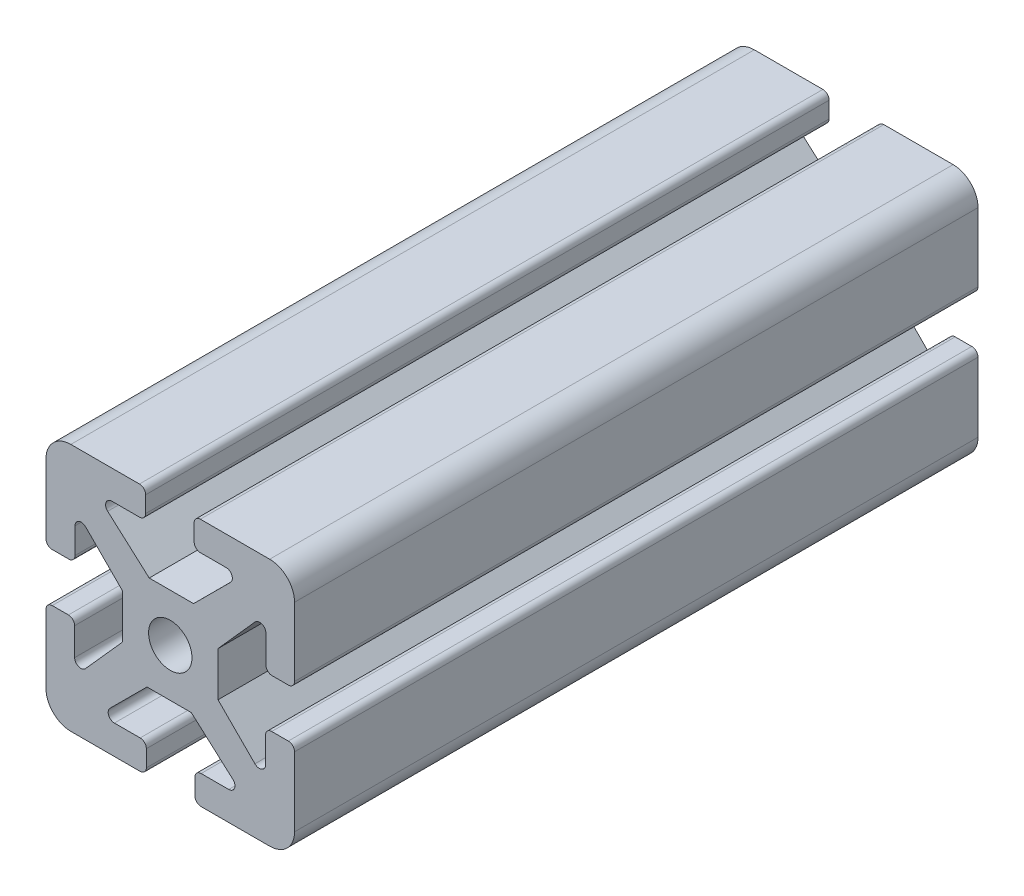
SolidWorks part; units mm, degrees
ref_plane "Front Plane" through (0, 0, 0) normal (0, 0, 1) x (1, 0, 0)
ref_plane "Top Plane" through (0, 0, 0) normal (0, 1, 0) x (1, 0, 0)
ref_plane "Right Plane" through (0, 0, 0) normal (1, 0, 0) x (0, 0, -1)
sketch "Sketch2" plane through (0, 0, 0) normal (0, 0, 1) x (1, 0, 0)
  line L0 (46.607, 139.3199) -> (233.0351, 139.3199) construction
  line L1 (0, 40) -> (40, 0) construction
  line L2 (0, 0) -> (40, 0) construction
  line L3 (0, 0) -> (0, 40) construction
  line L4 (0, 40) -> (40, 40) construction
  line L5 (40, 0) -> (40, 40) construction
  line L6 (0, 0) -> (40, 40) construction
  line L7 (19.4883, 27.6847) -> (23.7499, 27.6847)
  line L8 (23.7499, 27.6847) -> (29.6997, 33.625)
  line L9 (28.9931, 35.3327) -> (24.8456, 35.3327)
  line L10 (23.8456, 36.3327) -> (23.8456, 39)
  line L11 (24.8456, 40) -> (36, 40)
  line L12 (40, 36) -> (40, 24.9611)
  line L13 (39, 23.9611) -> (36.3883, 23.9611)
  line L14 (35.3883, 24.9611) -> (35.3883, 29.4086)
  line L15 (33.6417, 30.0739) -> (27.6847, 23.3888)
  line L16 (27.6847, 23.3888) -> (27.6847, 20.5117)
  line L17 (27.6847, 16.2501) -> (33.625, 10.3003)
  line L18 (30.0739, 6.3583) -> (23.3888, 12.3153)
  line L19 (27.6847, 20.5117) -> (27.6847, 16.2501)
  line L20 (35.3327, 11.0069) -> (35.3327, 15.1544)
  line L21 (36.3327, 16.1544) -> (39, 16.1544)
  line L22 (40, 15.1544) -> (40, 4)
  line L23 (36, 0) -> (24.9611, 0)
  line L24 (23.9611, 1) -> (23.9611, 3.6117)
  line L25 (24.9611, 4.6117) -> (29.4086, 4.6117)
  line L26 (23.3888, 12.3153) -> (20.5117, 12.3153)
  line L27 (16.2501, 12.3153) -> (10.3003, 6.375)
  line L28 (6.3583, 9.9261) -> (12.3153, 16.6112)
  line L29 (20.5117, 12.3153) -> (16.2501, 12.3153)
  line L30 (11.0069, 4.6673) -> (15.1544, 4.6673)
  line L31 (16.1544, 3.6673) -> (16.1544, 1)
  line L32 (15.1544, 0) -> (4, 0)
  line L33 (0, 4) -> (0, 15.0389)
  line L34 (1, 16.0389) -> (3.6117, 16.0389)
  line L35 (4.6117, 15.0389) -> (4.6117, 10.5914)
  line L36 (12.3153, 16.6112) -> (12.3153, 19.4883)
  line L37 (12.3153, 23.7499) -> (6.375, 29.6997)
  line L38 (9.9261, 33.6417) -> (16.6112, 27.6847)
  line L39 (12.3153, 19.4883) -> (12.3153, 23.7499)
  line L40 (4.6673, 28.9931) -> (4.6673, 24.8456)
  line L41 (3.6673, 23.8456) -> (1, 23.8456)
  line L42 (0, 24.8456) -> (0, 36)
  line L43 (4, 40) -> (15.0389, 40)
  line L44 (16.0389, 39) -> (16.0389, 36.3883)
  line L45 (15.0389, 35.3883) -> (10.5914, 35.3883)
  line L46 (16.6112, 27.6847) -> (19.4883, 27.6847)
  circle A1 centre (20, 20) radius 3.4925
  arc A2 (40, 24.9611) -> (39, 23.9611) centre (39, 24.9611) cw
  arc A3 (36.3883, 23.9611) -> (35.3883, 24.9611) centre (36.3883, 24.9611) cw
  arc A4 (24.8456, 35.3327) -> (23.8456, 36.3327) centre (24.8456, 36.3327) cw
  arc A5 (23.8456, 39) -> (24.8456, 40) centre (24.8456, 39) cw
  arc A6 (29.6997, 33.625) -> (28.9931, 35.3327) centre (28.9931, 34.3327) ccw
  arc A7 (35.3883, 29.4086) -> (33.6417, 30.0739) centre (34.3883, 29.4086) ccw
  arc A8 (40, 36) -> (36, 40) centre (36, 36) ccw
  arc A9 (35.3327, 15.1544) -> (36.3327, 16.1544) centre (36.3327, 15.1544) cw
  arc A10 (39, 16.1544) -> (40, 15.1544) centre (39, 15.1544) cw
  arc A11 (36, 0) -> (40, 4) centre (36, 4) ccw
  arc A12 (24.9611, 0) -> (23.9611, 1) centre (24.9611, 1) cw
  arc A13 (23.9611, 3.6117) -> (24.9611, 4.6117) centre (24.9611, 3.6117) cw
  arc A14 (29.4086, 4.6117) -> (30.0739, 6.3583) centre (29.4086, 5.6117) ccw
  arc A15 (33.625, 10.3003) -> (35.3327, 11.0069) centre (34.3327, 11.0069) ccw
  arc A16 (15.1544, 4.6673) -> (16.1544, 3.6673) centre (15.1544, 3.6673) cw
  arc A17 (16.1544, 1) -> (15.1544, 0) centre (15.1544, 1) cw
  arc A18 (0, 4) -> (4, 0) centre (4, 4) ccw
  arc A19 (0, 15.0389) -> (1, 16.0389) centre (1, 15.0389) cw
  arc A20 (3.6117, 16.0389) -> (4.6117, 15.0389) centre (3.6117, 15.0389) cw
  arc A21 (4.6117, 10.5914) -> (6.3583, 9.9261) centre (5.6117, 10.5914) ccw
  arc A22 (10.3003, 6.375) -> (11.0069, 4.6673) centre (11.0069, 5.6673) ccw
  arc A23 (4.6673, 24.8456) -> (3.6673, 23.8456) centre (3.6673, 24.8456) cw
  arc A24 (1, 23.8456) -> (0, 24.8456) centre (1, 24.8456) cw
  arc A25 (4, 40) -> (0, 36) centre (4, 36) ccw
  arc A26 (15.0389, 40) -> (16.0389, 39) centre (15.0389, 39) cw
  arc A27 (16.0389, 36.3883) -> (15.0389, 35.3883) centre (15.0389, 36.3883) cw
  arc A28 (10.5914, 35.3883) -> (9.9261, 33.6417) centre (10.5914, 34.3883) ccw
  arc A29 (6.375, 29.6997) -> (4.6673, 28.9931) centre (5.6673, 28.9931) ccw
  point P24 (40, 23.9611)
  point P31 (23.8456, 40)
  dimension "D1" = 40
  dimension "D3" = 1
  dimension "D4" = 4
  dimension "D2" = 40
  dimension "D5" = 4
extrude "Boss-Extrude1" add sketch "Sketch2" along normal blind 110
